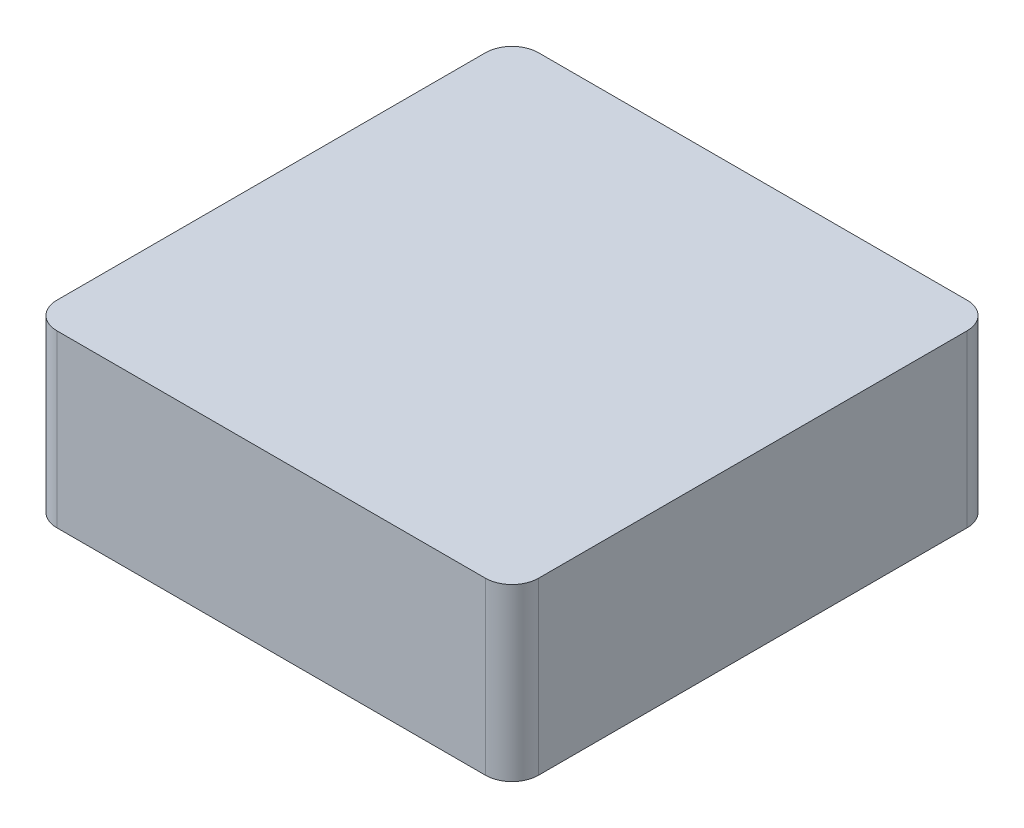
SolidWorks part; units mm, degrees
ref_plane "Front Plane" through (0, 0, 0) normal (0, 0, 1) x (1, 0, 0)
ref_plane "Top Plane" through (0, 0, 0) normal (0, 1, 0) x (1, 0, 0)
ref_plane "Right Plane" through (0, 0, 0) normal (1, 0, 0) x (0, 0, -1)
sketch "Sketch1" plane through (0, 0, 0) normal (0, 1, 0) x (1, 0, 0)
  line L1 (0, 0) -> (127, 0)
  line L2 (0, 0) -> (0, 127)
  line L3 (0, 127) -> (127, 127)
  line L4 (127, 0) -> (127, 127)
  dimension "D1" = 127
  dimension "D2" = 127
extrude "Boss-Extrude1" add sketch "Sketch1" along normal blind 45
fillet "Fillet1" radius 7 4 edges at (127, 22.5, -127) (0, 22.5, -127) (127, 22.5, 0) (0, 22.5, 0)
